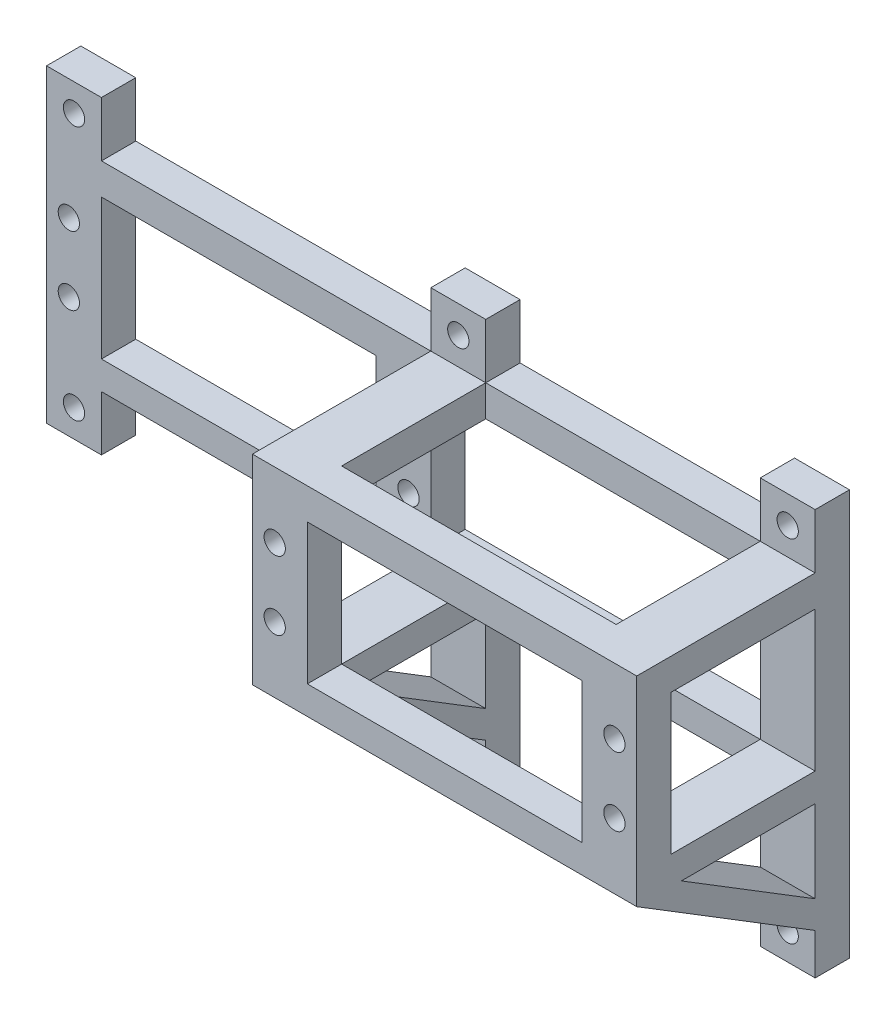
SolidWorks part; units mm, degrees
ref_plane "Front Plane" through (0, 0, 0) normal (0, 0, 1) x (1, 0, 0)
ref_plane "Top Plane" through (0, 0, 0) normal (0, 1, 0) x (1, 0, 0)
ref_plane "Right Plane" through (0, 0, 0) normal (1, 0, 0) x (0, 0, -1)
sketch "Sketch1" plane through (0, 0, 0) normal (0, 0, 1) x (1, 0, 0)
  line L1 (-39.7436, 2.0564) -> (72.2564, 2.0564)
  line L2 (-39.7436, 2.0564) -> (-39.7436, -2.0564)
  line L3 (-39.7436, -2.0564) -> (72.2564, -2.0564)
  line L4 (72.2564, 2.0564) -> (72.2564, -2.0564)
  point P0 (0, 0)
  dimension "D1" = 112
extrude "Boss-Extrude1" add sketch "Sketch1" against normal blind 5
sketch "Sketch2" plane through (0, 2.0564, 0) normal (0, 1, 0) x (1, 0, 0)
  line L0 (72.2564, 5) -> (-39.7436, 5) construction
  line L1 (-39.7436, 5) -> (-31.7436, 5)
  line L2 (-39.7436, 5) -> (-39.7436, 0)
  line L3 (-39.7436, 0) -> (-31.7436, 0)
  line L4 (-31.7436, 5) -> (-31.7436, 0)
  line L5 (72.2564, 0) -> (-39.7436, 0) construction
  line L7 (8.2564, 5) -> (16.2564, 5)
  line L8 (8.2564, 5) -> (8.2564, 0)
  line L9 (8.2564, 0) -> (16.2564, 0)
  line L10 (16.2564, 5) -> (16.2564, 0)
  line L11 (64.2564, 5) -> (72.2564, 5)
  line L12 (64.2564, 5) -> (64.2564, 0)
  line L13 (64.2564, 0) -> (72.2564, 0)
  line L14 (72.2564, 5) -> (72.2564, 0)
  dimension "D1" = 48
  dimension "D2" = 40
  dimension "D4" = 0
extrude "Boss-Extrude2" add sketch "Sketch2" along normal blind 25
sketch "Sketch3" plane through (-31.7436, 0, 0) normal (1, 0, 0) x (0, 0, -1)
  line L0 (5, 27.0564) -> (5, 2.0564) construction
  line L1 (0, 27.0564) -> (5, 27.0564)
  line L2 (0, 27.0564) -> (0, 22.5)
  line L3 (0, 22.5) -> (5, 22.5)
  line L4 (5, 27.0564) -> (5, 22.5)
extrude "Boss-Extrude3" add sketch "Sketch3" along normal blind 45 contours L1 L4 L3 L2
sketch "Sketch4" plane through (64.2564, 0, 0) normal (-1, 0, 0) x (0, 0, 1)
  line L1 (-5, 27.0564) -> (0, 27.0564)
  line L2 (-5, 27.0564) -> (-5, 22.5)
  line L3 (-5, 22.5) -> (0, 22.5)
  line L4 (0, 27.0564) -> (0, 22.5)
extrude "Boss-Extrude5" add sketch "Sketch4" along normal blind 51 contours L3 L4 L1 L2
sketch "Sketch6" plane through (0, 0, 0) normal (0, 0, 1) x (1, 0, 0)
  line L1 (24.2564, 2.0564) -> (16.2564, 2.0564)
  line L2 (24.2564, 2.0564) -> (24.2564, -2.0564)
  line L3 (24.2564, -2.0564) -> (16.2564, -2.0564)
  line L4 (16.2564, 2.0564) -> (16.2564, -2.0564)
  line L5 (-39.7436, -2.0564) -> (72.2564, -2.0564) construction
  line L6 (-39.7436, 27.0564) -> (72.2564, 27.0564) construction
  line L7 (24.2564, 22.5) -> (16.2564, 22.5)
  line L8 (24.2564, 22.5) -> (24.2564, 27.0564)
  line L9 (24.2564, 27.0564) -> (16.2564, 27.0564)
  line L10 (16.2564, 22.5) -> (16.2564, 27.0564)
  line L12 (64.2564, 22.5) -> (72.2564, 22.5)
  line L13 (64.2564, 22.5) -> (64.2564, 27.0564)
  line L14 (64.2564, 27.0564) -> (72.2564, 27.0564)
  line L15 (72.2564, 22.5) -> (72.2564, 27.0564)
  line L16 (64.2564, 2.0564) -> (72.2564, 2.0564)
  line L17 (64.2564, 2.0564) -> (64.2564, -2.0564)
  line L18 (64.2564, -2.0564) -> (72.2564, -2.0564)
  line L19 (72.2564, 2.0564) -> (72.2564, -2.0564)
  dimension "D1" = 8
extrude "Boss-Extrude6" add sketch "Sketch6" along normal blind 26
sketch "Sketch7" plane through (0, 2.0564, 0) normal (0, 1, 0) x (1, 0, 0)
  line L0 (24.2564, -26) -> (24.2564, 0) construction
  line L1 (16.2564, -26) -> (24.2564, -26)
  line L2 (16.2564, -26) -> (16.2564, -21)
  line L3 (16.2564, -21) -> (24.2564, -21)
  line L4 (24.2564, -26) -> (24.2564, -21)
extrude "Boss-Extrude7" add sketch "Sketch7" along normal blind 21 contours L3 L4 L1 L2
sketch "Sketch8" plane through (0, 2.0564, 0) normal (0, 1, 0) x (1, 0, 0)
  line L0 (72.2564, -26) -> (72.2564, 0) construction
  line L1 (64.2564, -26) -> (72.2564, -26)
  line L2 (64.2564, -26) -> (64.2564, -21)
  line L3 (64.2564, -21) -> (72.2564, -21)
  line L4 (72.2564, -26) -> (72.2564, -21)
extrude "Boss-Extrude8" add sketch "Sketch8" along normal blind 21 contours L3 L4 L1 L2
sketch "Sketch9" plane through (16.2564, 0, 0) normal (1, 0, 0) x (0, 0, -1)
  line L1 (-26, 27.0564) -> (-21, 27.0564)
  line L2 (-26, 27.0564) -> (-26, 22.5)
  line L3 (-26, 22.5) -> (-21, 22.5)
  line L4 (-21, 27.0564) -> (-21, 22.5)
  line L5 (-21, 2.0564) -> (-26, 2.0564)
  line L6 (-21, 2.0564) -> (-21, -2.0564)
  line L7 (-21, -2.0564) -> (-26, -2.0564)
  line L8 (-26, 2.0564) -> (-26, -2.0564)
extrude "Boss-Extrude9" add sketch "Sketch9" along normal blind 51
sketch "Sketch10" plane through (0, 0, 0) normal (0, 0, 1) x (1, 0, 0)
  line L0 (8.2564, 22.5) -> (8.2564, 2.0564) construction
  line L1 (-31.7436, 22.5) -> (-31.7436, 2.0564) construction
  line L2 (8.2564, 22.5) -> (-31.7436, 22.5) construction
  circle A2 centre (-36.4936, 17.5) radius 1.55
  circle A3 centre (-36.4936, 7.5) radius 1.55
  circle A4 centre (13.0064, 17.5) radius 1.55
  circle A5 centre (13.0064, 7.5) radius 1.55
  dimension "D1" = 0
  dimension "D2" = 49.5
  dimension "D3" = 40
  dimension "D4" = 0
  dimension "D5" = 4.75
  dimension "D6" = 5
sketch "Sketch12" plane through (0, 0, 26) normal (0, 0, 1) x (1, 0, 0)
  line L0 (64.2564, 22.5) -> (24.2564, 22.5) construction
  line L2 (24.2564, 2.0564) -> (24.2564, 22.5) construction
  circle A0 centre (19.5064, 17.5) radius 1.55
  circle A1 centre (19.505, 7.5) radius 1.55
  circle A2 centre (69.0064, 17.5) radius 1.55
  circle A3 centre (69.0064, 7.5) radius 1.55
  dimension "D1" = 49.5
  dimension "D7" = 4.75
  dimension "D2" = 0
  dimension "D3" = 5
  dimension "D4" = 10
  dimension "D5" = 10
  dimension "D6" = 5
extrude "Cut-Extrude1" cut sketch "Sketch10" against normal blind 10
extrude "Cut-Extrude2" cut sketch "Sketch12" against normal blind 10
sketch "Sketch13" plane through (0, 27.0564, 0) normal (0, 1, 0) x (1, 0, 0)
  line L0 (-39.7436, 0) -> (16.2564, 0) construction
  line L1 (-39.7436, 5) -> (-31.7436, 5)
  line L2 (-39.7436, 5) -> (-39.7436, 0)
  line L3 (-39.7436, 0) -> (-31.7436, 0)
  line L4 (-31.7436, 5) -> (-31.7436, 0)
  line L5 (72.2564, 5) -> (-39.7436, 5) construction
  line L6 (16.2564, 5) -> (24.2564, 5)
  line L7 (16.2564, 5) -> (16.2564, 0)
  line L8 (16.2564, 0) -> (24.2564, 0)
  line L9 (24.2564, 5) -> (24.2564, 0)
  line L11 (72.2564, 5) -> (64.2564, 5)
  line L12 (72.2564, 5) -> (72.2564, 0)
  line L13 (72.2564, 0) -> (64.2564, 0)
  line L14 (64.2564, 5) -> (64.2564, 0)
extrude "Boss-Extrude10" add sketch "Sketch13" along normal blind 8
sketch "Sketch14" plane through (0, -2.0564, 0) normal (0, -1, 0) x (1, 0, 0)
  line L0 (-39.7436, -5) -> (72.2564, -5) construction
  line L1 (-39.7436, 0) -> (-31.7436, 0)
  line L2 (-39.7436, 0) -> (-39.7436, -5)
  line L3 (-39.7436, -5) -> (-31.7436, -5)
  line L4 (-31.7436, 0) -> (-31.7436, -5)
extrude "Boss-Extrude11" add sketch "Sketch14" along normal blind 8
sketch "Sketch15" plane through (0, -2.0564, 0) normal (0, -1, 0) x (1, 0, 0)
  line L1 (16.2564, 0) -> (24.2564, 0)
  line L2 (16.2564, 0) -> (16.2564, -5)
  line L3 (16.2564, -5) -> (24.2564, -5)
  line L4 (24.2564, 0) -> (24.2564, -5)
  line L5 (64.2564, 0) -> (72.2564, 0)
  line L6 (64.2564, 0) -> (64.2564, -5)
  line L7 (64.2564, -5) -> (72.2564, -5)
  line L8 (72.2564, 0) -> (72.2564, -5)
extrude "Boss-Extrude12" add sketch "Sketch15" along normal blind 22
sketch "Sketch16" plane through (16.2564, 0, 0) normal (-1, 0, 0) x (0, 0, 1)
  line L0 (0, -18.0564) -> (0, -14.0564)
  line L1 (0, -18.0564) -> (26, -2.0564)
  line L2 (0, -14.0564) -> (26, 1.9436)
  line L3 (26, -2.0564) -> (26, 1.9436)
  line L4 (0, -24.0564) -> (0, -2.0564) construction
  dimension "D1" = 12
extrude "Boss-Extrude13" add sketch "Sketch16" against normal blind 8 contours L2 L3 L1 L0
sketch "Sketch17" plane through (72.2564, 0, 0) normal (1, 0, 0) x (0, 0, -1)
  line L0 (0, -18.0564) -> (0, -14.0564)
  line L1 (0, -18.0564) -> (-26, -2.0564)
  line L2 (0, -14.0564) -> (-26, 1.9436)
  line L3 (-26, -2.0564) -> (-26, 1.9436)
extrude "Boss-Extrude14" add sketch "Sketch17" against normal blind 8 contours L1 L3 L2 L0
sketch "Sketch18" plane through (0, 0, 0) normal (0, 0, 1) x (1, 0, 0)
  line L0 (-31.7436, 35.0564) -> (-31.7436, 27.0564) construction
  line L1 (-39.7436, 35.0564) -> (-31.7436, 35.0564) construction
  circle A0 centre (-35.7436, 31.0564) radius 1.55
  dimension "D1" = 4
  dimension "D2" = 4
extrude "Cut-Extrude3" cut sketch "Sketch18" against normal blind 8 contours A0
sketch "Sketch19" plane through (0, 0, 0) normal (0, 0, 1) x (1, 0, 0)
  line L0 (16.2564, 35.0564) -> (24.2564, 35.0564) construction
  line L1 (16.2564, 35.0564) -> (16.2564, 27.0564) construction
  circle A0 centre (20.2564, 31.0564) radius 1.55
  dimension "D1" = 4
  dimension "D2" = 4
extrude "Cut-Extrude4" cut sketch "Sketch19" against normal blind 8 contours A0
sketch "Sketch20" plane through (0, 0, 0) normal (0, 0, 1) x (1, 0, 0)
  line L0 (72.2564, 35.0564) -> (72.2564, 27.0564) construction
  line L1 (64.2564, 35.0564) -> (72.2564, 35.0564) construction
  circle A0 centre (68.2564, 31.0564) radius 1.55
  dimension "D1" = 4
  dimension "D2" = 4
extrude "Cut-Extrude5" cut sketch "Sketch20" against normal blind 8 contours A0
sketch "Sketch21" plane through (0, 0, 0) normal (0, 0, 1) x (1, 0, 0)
  line L0 (-31.7436, -10.0564) -> (-39.7436, -10.0564) construction
  line L1 (-31.7436, -10.0564) -> (-31.7436, -2.0564) construction
  circle A0 centre (-35.7436, -6.0564) radius 1.55
  dimension "D1" = 4
  dimension "D2" = 4
extrude "Cut-Extrude6" cut sketch "Sketch21" against normal blind 8 contours A0
sketch "Sketch22" plane through (0, 0, 0) normal (0, 0, 1) x (1, 0, 0)
  line L0 (24.2564, -24.0564) -> (24.2564, -18.0564) construction
  line L1 (24.2564, -24.0564) -> (16.2564, -24.0564) construction
  circle A0 centre (20.2564, -20.0564) radius 1.55
  dimension "D1" = 4
  dimension "D2" = 4
extrude "Cut-Extrude7" cut sketch "Sketch22" against normal blind 8 contours A0
sketch "Sketch23" plane through (0, 0, 0) normal (0, 0, 1) x (1, 0, 0)
  line L0 (72.2564, -24.0564) -> (64.2564, -24.0564) construction
  line L1 (72.2564, -24.0564) -> (72.2564, -18.0564) construction
  circle A0 centre (68.2564, -20.0564) radius 1.55
  dimension "D1" = 4
  dimension "D2" = 4
extrude "Cut-Extrude8" cut sketch "Sketch23" against normal blind 8 contours A0
